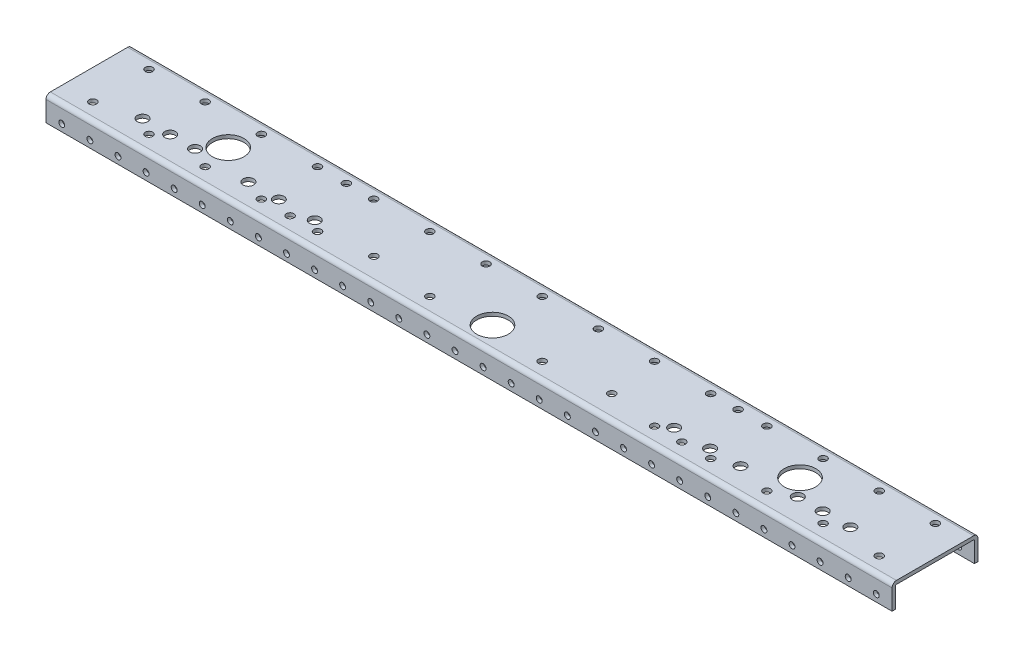
SolidWorks part; units mm, degrees
ref_plane "Front Plane" through (0, 0, 0) normal (0, 0, 1) x (1, 0, 0)
ref_plane "Top Plane" through (0, 0, 0) normal (0, 1, 0) x (1, 0, 0)
ref_plane "Right Plane" through (0, 0, 0) normal (1, 0, 0) x (0, 0, -1)
ref_plane "Plane1" through (0, -19.05, 0) normal (0, -1, 0) x (1, 0, 0)
sketch "Sketch1" plane through (0, -19.05, 0) normal (0, -1, 0) x (1, 0, 0)
  line L0 (812.8, 3.937) -> (0, 3.937)
  line L1 (0, 3.937) -> (0, -73.787)
  line L2 (0, -73.787) -> (812.8, -73.787)
  line L3 (812.8, -73.787) -> (812.8, 3.937)
extrude "Boss-Extrude1" add sketch "Sketch1" against normal blind 22.225
sketch "Sketch2" plane through (0, 0, 0) normal (-1, 0, 0) x (0, 0, 1)
  line L0 (-70.612, -19.05) -> (0.762, -19.05)
  line L1 (0.762, -19.05) -> (0.762, 0)
  line L2 (0.762, 0) -> (-70.612, 0)
  line L3 (-70.612, 0) -> (-70.612, -19.05)
extrude "Cut-Extrude1" cut sketch "Sketch2" against normal through all
hole_wizard "Hole1" positions "Sketch4" profile "Sketch3" legacy
sketch "Sketch4" plane through (0, 0, 0) normal (0, -1, 0) x (-1, 0, 0)
  point P0 (-568.9249, 19.05)
  point P1 (-601.4385, 19.05)
  point P2 (-628.9477, 19.05)
  point P3 (-243.8751, 19.05)
  point P4 (-211.3615, 19.05)
  point P5 (-183.8523, 19.05)
  point P6 (-678.9442, 20.828)
  point P7 (-701.4504, 20.828)
  point P8 (-726.4609, 20.828)
  point P9 (-133.8558, 20.828)
  point P10 (-111.3496, 20.828)
  point P11 (-86.3391, 20.828)
sketch "Sketch3" plane through (568.9249, 0, -19.05) normal (1, 0, 0) x (0, 0, -1)
  line L0 (0, 0) -> (0, 3.175)
  line L1 (0, 3.175) -> (4.826, 3.175)
  line L2 (4.826, 3.175) -> (4.826, 0)
  line L3 (4.826, 0) -> (0, 0)
  line L4 (0, 110) -> (0, -10) construction
  dimension "Diameter" = 9.652
  dimension "Depth" = 3.175
hole_wizard "Hole2" positions "Sketch6" profile "Sketch5" legacy
sketch "Sketch6" plane through (0, 0, 0) normal (0, -1, 0) x (-1, 0, 0)
  point P0 (-664.9708, 36.83)
  point P1 (-147.8292, 36.83)
  point P2 (-406.4, 17.272)
sketch "Sketch5" plane through (664.9708, 0, -36.83) normal (1, 0, 0) x (0, 0, -1)
  line L0 (0, 0) -> (0, 3.175)
  line L1 (0, 3.175) -> (14.2875, 3.175)
  line L2 (14.2875, 3.175) -> (14.2875, 0)
  line L3 (14.2875, 0) -> (0, 0)
  line L4 (0, 110) -> (0, -10) construction
  dimension "Diameter" = 28.575
  dimension "Depth" = 3.175
hole_wizard "H (0.266) Diameter Hole1" positions "Sketch8" profile "Sketch7" hole size "H" standard "ANSI Inch"
sketch "Sketch8" plane through (0, 0, 0) normal (0, -1, 0) x (-1, 0, 0)
  point P0 (-762, 11.43)
  point P1 (-762, 62.23)
  point P2 (-711.2, 11.43)
  point P3 (-711.2, 62.23)
  point P4 (-660.4, 11.43)
  point P5 (-660.4, 62.23)
  point P6 (-609.6, 11.43)
  point P7 (-609.6, 62.23)
  point P8 (-558.8, 11.43)
  point P9 (-558.8, 62.23)
  point P10 (-152.4, 11.43)
  point P11 (-203.2, 62.23)
  point P12 (-203.2, 11.43)
  point P13 (-254, 62.23)
  point P14 (-50.8, 11.43)
  point P15 (-101.6, 62.23)
  point P16 (-101.6, 11.43)
  point P17 (-152.4, 62.23)
  point P18 (-254, 11.43)
  point P19 (-304.8, 62.23)
  point P20 (-355.6, 62.23)
  point P21 (-355.6, 11.43)
  point P22 (-508, 62.23)
  point P23 (-457.2, 11.43)
  point P24 (-457.2, 62.23)
  point P25 (-406.4, 62.23)
  point P26 (-50.8, 62.23)
  point P27 (-583.5384, 62.23)
  point P28 (-583.5384, 11.43)
  point P29 (-229.2616, 11.43)
  point P30 (-229.2616, 62.23)
  point P31 (-513.9255, 17.5473)
  point P32 (-298.8745, 17.5473)
sketch "Sketch7" plane through (762, 0, -11.43) normal (1, 0, 0) x (0, 0, -1)
  line L0 (0, 0) -> (0, 3.175)
  line L1 (0, 3.175) -> (3.3782, 3.175)
  line L2 (3.3782, 3.175) -> (3.3782, 0)
  line L5 (3.3782, 0) -> (0, 0)
  line L11 (0, -6.35) -> (0, 107.95) construction
  dimension "Thru Hole Dia." = 6.7564
  dimension "Thru Hole Depth" = 3.175
hole_wizard "#10 Clearance Hole1" positions "Sketch10" profile "Sketch9" hole size "#10" standard "ANSI Inch"
sketch "Sketch10" plane through (0, 0, 0.762) normal (0, 0, -1) x (-1, 0, 0)
  point P0 (-12.7, -12.7)
  point P1 (-800.1, -12.7)
sketch "Sketch9" plane through (12.7, -12.7, 0.762) normal (1, 0, 0) x (0, 1, 0)
  line L0 (0, 0) -> (0, 3.175)
  line L1 (0, 3.175) -> (2.667, 3.175)
  line L2 (2.667, 3.175) -> (2.667, 0)
  line L5 (2.667, 0) -> (0, 0)
  line L11 (0, -6.35) -> (0, 107.95) construction
  dimension "Thru Hole Dia." = 5.334
  dimension "Thru Hole Depth" = 3.175
hole_wizard "#10 Clearance Hole2" positions "Sketch12" profile "Sketch11" hole size "#10" standard "ANSI Inch"
sketch "Sketch12" plane through (0, 0, 3.937) normal (0, 0, 1) x (1, 0, 0)
  point P0 (63.5, -12.7)
  point P1 (38.1, -12.7)
  point P2 (88.9, -12.7)
  point P3 (114.3, -12.7)
  point P4 (139.7, -12.7)
  point P5 (165.1, -12.7)
  point P6 (190.5, -12.7)
  point P7 (215.9, -12.7)
  point P8 (241.3, -12.7)
  point P9 (266.7, -12.7)
  point P10 (292.1, -12.7)
  point P11 (317.5, -12.7)
  point P12 (342.9, -12.7)
  point P13 (368.3, -12.7)
  point P14 (393.7, -12.7)
  point P15 (419.1, -12.7)
  point P16 (444.5, -12.7)
  point P17 (469.9, -12.7)
  point P18 (495.3, -12.7)
  point P19 (520.7, -12.7)
  point P20 (546.1, -12.7)
  point P21 (571.5, -12.7)
  point P22 (596.9, -12.7)
  point P23 (622.3, -12.7)
  point P24 (647.7, -12.7)
  point P25 (673.1, -12.7)
  point P26 (698.5, -12.7)
  point P27 (723.9, -12.7)
  point P28 (749.3, -12.7)
  point P29 (774.7, -12.7)
sketch "Sketch11" plane through (63.5, -12.7, 3.937) normal (1, 0, 0) x (0, -1, 0)
  line L0 (0, 0) -> (0, 3.175)
  line L1 (0, 3.175) -> (2.667, 3.175)
  line L2 (2.667, 3.175) -> (2.667, 0)
  line L5 (2.667, 0) -> (0, 0)
  line L11 (0, -6.35) -> (0, 107.95) construction
  dimension "Thru Hole Dia." = 5.334
  dimension "Thru Hole Depth" = 3.175
hole_wizard "#10 Clearance Hole3" positions "Sketch14" profile "Sketch13" hole size "#10" standard "ANSI Inch"
sketch "Sketch14" plane through (0, 0, -70.612) normal (0, 0, 1) x (1, 0, 0)
  point P0 (800.1, -12.7)
  point P1 (774.7, -12.7)
  point P2 (749.3, -12.7)
  point P3 (723.9, -12.7)
  point P4 (698.5, -12.7)
  point P5 (673.1, -12.7)
  point P6 (647.7, -12.7)
  point P7 (622.3, -12.7)
  point P8 (596.9, -12.7)
  point P9 (571.5, -12.7)
  point P10 (546.1, -12.7)
  point P11 (520.7, -12.7)
  point P12 (495.3, -12.7)
  point P13 (469.9, -12.7)
  point P14 (444.5, -12.7)
  point P15 (419.1, -12.7)
  point P16 (393.7, -12.7)
  point P17 (368.3, -12.7)
  point P18 (342.9, -12.7)
  point P19 (317.5, -12.7)
  point P20 (292.1, -12.7)
  point P21 (266.7, -12.7)
  point P22 (241.3, -12.7)
  point P23 (215.9, -12.7)
  point P24 (190.5, -12.7)
  point P25 (165.1, -12.7)
  point P26 (139.7, -12.7)
  point P27 (114.3, -12.7)
  point P28 (88.9, -12.7)
  point P29 (63.5, -12.7)
  point P30 (38.1, -12.7)
  point P31 (12.7, -12.7)
sketch "Sketch13" plane through (800.1, -12.7, -70.612) normal (1, 0, 0) x (0, -1, 0)
  line L0 (0, 0) -> (0, 3.175)
  line L1 (0, 3.175) -> (2.667, 3.175)
  line L2 (2.667, 3.175) -> (2.667, 0)
  line L5 (2.667, 0) -> (0, 0)
  line L11 (0, -6.35) -> (0, 107.95) construction
  dimension "Thru Hole Dia." = 5.334
  dimension "Thru Hole Depth" = 3.175
chamfer "Chamfer1" distance 3.175 angle 45 4 edges at (812.8, -19.05, -72.1995) (812.8, -19.05, 2.3495) (0, -19.05, -72.1995) (0, -19.05, 2.3495)
fillet "Fillet1" radius 0.762 2 edges at (406.4, 0, 0.762) (406.4, 0, -70.612)
fillet "Fillet2" radius 3.937 2 edges at (406.4, 3.175, 3.937) (406.4, 3.175, -73.787)
sketch "Sketch15" plane through (0, 3.175, 0) normal (0, 1, 0) x (1, 0, 0)
  line L0 (0, 73.787) -> (812.8, 73.787) construction
  line L1 (0, -3.937) -> (23.8125, -3.937)
  line L2 (0, -3.937) -> (0, 73.787)
  line L3 (0, 73.787) -> (23.8125, 73.787)
  line L4 (23.8125, -3.937) -> (23.8125, 73.787)
  line L5 (812.8, -3.937) -> (0, -3.937) construction
  line L6 (812.8, 73.787) -> (788.9875, 73.787)
  line L7 (812.8, 73.787) -> (812.8, -3.937)
  line L8 (812.8, -3.937) -> (788.9875, -3.937)
  line L9 (788.9875, 73.787) -> (788.9875, -3.937)
  dimension "D1" = 765.175
extrude "Cut-Extrude2" cut sketch "Sketch15" against normal up to next
